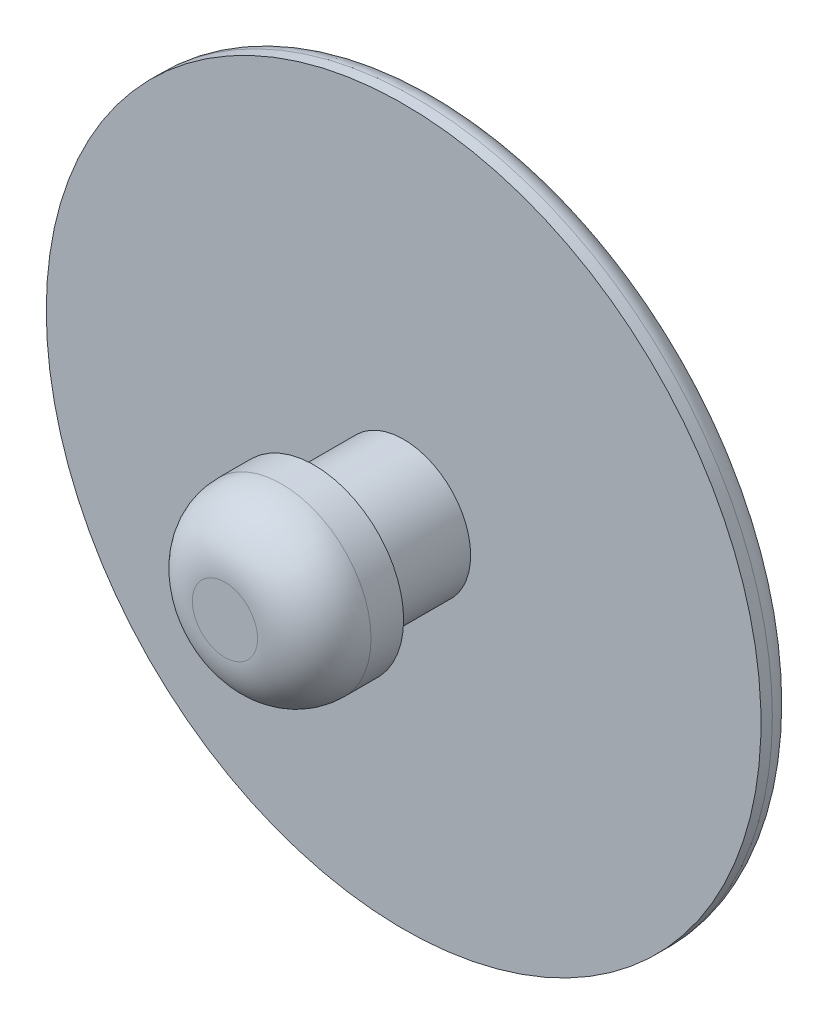
SolidWorks part; units mm, degrees
ref_plane "Front Plane" through (0, 0, 0) normal (0, 0, 1) x (1, 0, 0)
ref_plane "Top Plane" through (0, 0, 0) normal (0, 1, 0) x (1, 0, 0)
ref_plane "Right Plane" through (0, 0, 0) normal (1, 0, 0) x (0, 0, -1)
sketch "Sketch1" plane through (0, 0, 0) normal (0, 0, 1) x (1, 0, 0)
  circle A0 centre (0, 0) radius 8
  dimension "D1" = 16
extrude "Boss-Extrude1" add sketch "Sketch1" along normal blind 0.762
fillet "Fillet1" radius 0.508 1 edges at (8, 0, 0)
sketch "Sketch2" plane through (0, 0, 0.762) normal (0, 0, 1) x (1, 0, 0)
  circle A0 centre (0, 0) radius 1.5
  dimension "D1" = 3
extrude "Boss-Extrude2" add sketch "Sketch2" along normal blind 2
sketch "Sketch3" plane through (0, 0, 2.762) normal (0, 0, 1) x (1, 0, 0)
  circle A0 centre (0, 0) radius 2
  dimension "D1" = 4
extrude "Boss-Extrude3" add sketch "Sketch3" along normal blind 2
fillet "Fillet2" radius 1.27 1 edges at (2, 0, 4.762)
